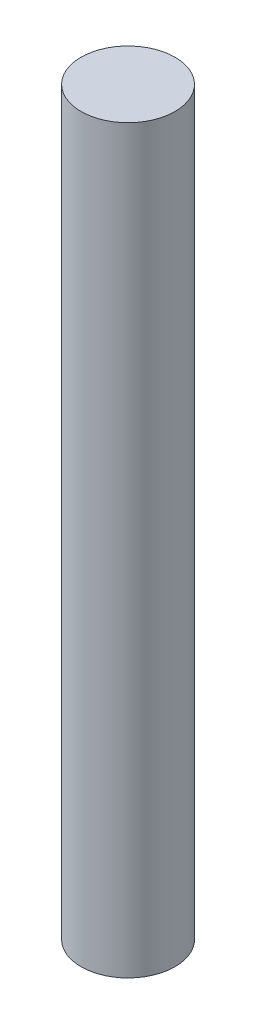
SolidWorks part; units mm, degrees
material "PLA"
ref_plane "Front Plane" through (0, 0, 0) normal (0, 0, 1) x (1, 0, 0)
ref_plane "Top Plane" through (0, 0, 0) normal (0, 1, 0) x (1, 0, 0)
ref_plane "Right Plane" through (0, 0, 0) normal (1, 0, 0) x (0, 0, -1)
sketch "Sketch1" plane through (0, 0, 0) normal (0, 1, 0) x (1, 0, 0)
  circle A0 centre (0, 0) radius 3.175
  dimension "D1" = 6.35
extrude "Boss-Extrude1" add sketch "Sketch1" along normal up to surface (50.025 mm away)
